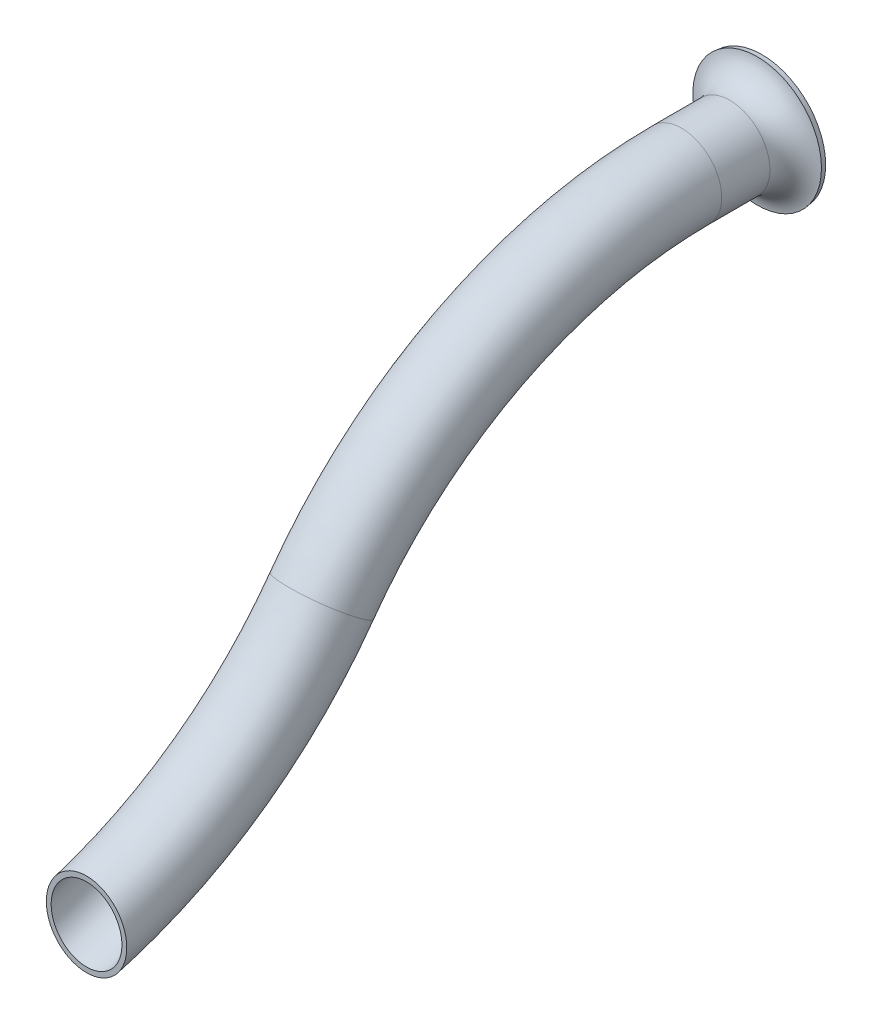
SolidWorks part; units mm, degrees
material "AISI Type 316L stainless steel"
ref_plane "Front Plane" through (0, 0, 0) normal (0, 0, 1) x (1, 0, 0)
ref_plane "Top Plane" through (0, 0, 0) normal (0, 1, 0) x (1, 0, 0)
ref_plane "Right Plane" through (0, 0, 0) normal (1, 0, 0) x (0, 0, -1)
sketch "Sketch1" plane through (0, 0, 0) normal (1, 0, 0) x (0, 0, -1)
  line L0 (0, 0) -> (-92.1057, 0) construction
  line L1 (-3, 23) -> (0, 23)
  line L2 (0, 38.1089) -> (0, 0) construction
  line L3 (-40, 36.7756) -> (-40, -16.7768) construction
  arc A0 (-3, 23) -> (-25.3663, 11.5) centre (-3, -4.5) ccw
  arc A1 (-25.3663, 11.5) -> (-40, 1.1095) centre (-47.7325, 27.5) cw
  arc A2 (-40, 1.1095) -> (-47.7325, 0) centre (-47.7325, 27.5) cw
  dimension "D1" = 27.5
  dimension "D2" = 3
  dimension "D3" = 23
  dimension "D4" = 40
sketch "Sketch2" plane through (0, 0, 0) normal (0, 0, 1) x (1, 0, 0)
  circle A0 centre (0, 23) radius 2.5
  circle A1 centre (0, 23) radius 2.2
  dimension "D1" = 0.3
  dimension "D2" = 5
sweep "Sweep1" add profiles "Sketch2" path "Sketch1"
sketch "Sketch3" plane through (0, 0, 0) normal (1, 0, 0) x (0, 0, -1)
  line L0 (-47.7325, 2.5) -> (-47.7325, -2.5) construction
  line L1 (-47.7325, -2.5) -> (-40, -2.5)
  line L2 (-47.7325, -2.5) -> (-47.7325, 4.5)
  line L3 (-47.7325, 4.5) -> (-40, 4.5)
  line L4 (-40, -2.5) -> (-40, 4.5)
  dimension "D1" = 40
  dimension "D2" = 7
extrude "Cut-Extrude1" cut sketch "Sketch3" against normal mid plane 10
sketch "Sketch4" plane through (0, 0, 0) normal (1, 0, 0) x (0, 0, -1)
  line L0 (0, 23) -> (4.6415, 23) construction
  line L1 (0, 20.5) -> (0, 25.5) construction
  line L2 (0, 25.2) -> (0, 25.5)
  line L3 (2, 26.9622) -> (1.7024, 27)
  arc A0 (0, 25.5) -> (1.7024, 27) centre (0, 27.216) ccw
  arc A1 (0, 25.2) -> (2, 26.9622) centre (0, 27.216) ccw
  dimension "D1" = 8
  dimension "D2" = 2
  dimension "D3" = 0.3
revolve "Revolve1" add sketch "Sketch4" angle 360 about L0
